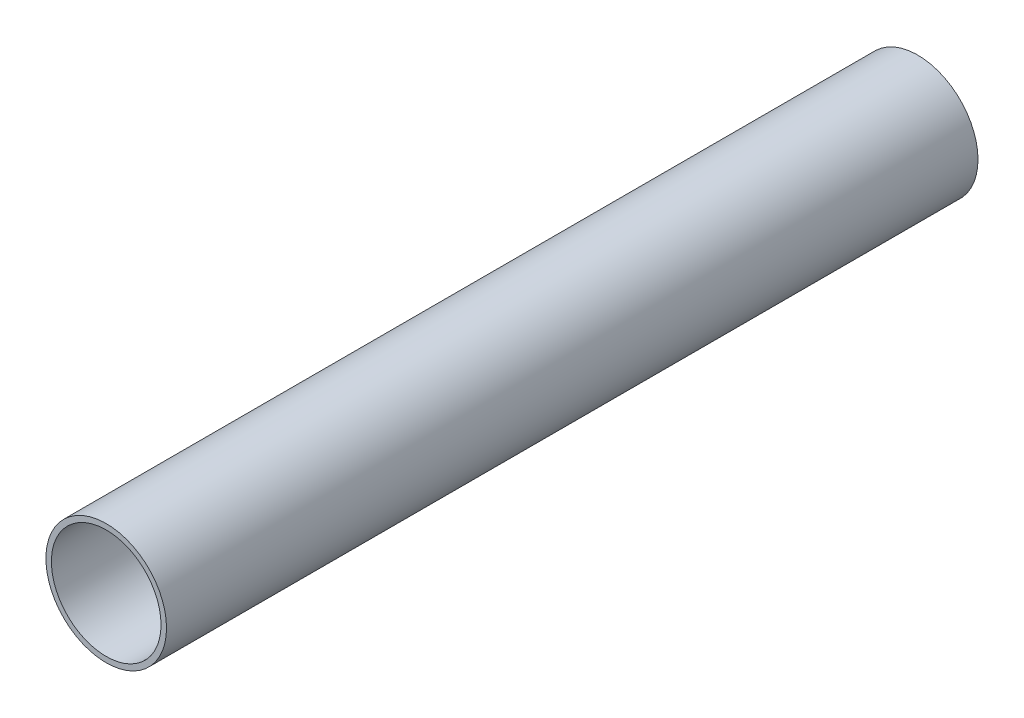
SolidWorks part; units mm, degrees
material "6061 Alloy"
ref_plane "Front Plane" through (0, 0, 0) normal (0, 0, 1) x (1, 0, 0)
ref_plane "Top Plane" through (0, 0, 0) normal (0, 1, 0) x (1, 0, 0)
ref_plane "Right Plane" through (0, 0, 0) normal (1, 0, 0) x (0, 0, -1)
sketch "Sketch2" plane through (0, 0, 0) normal (0, 0, 1) x (1, 0, 0)
  circle A0 centre (0, 0) radius 34.925
  circle A1 centre (0, 0) radius 31.75
  dimension "D1" = 69.85
  dimension "D2" = 63.5
extrude "Boss-Extrude1" add sketch "Sketch2" along normal mid plane 469.9
